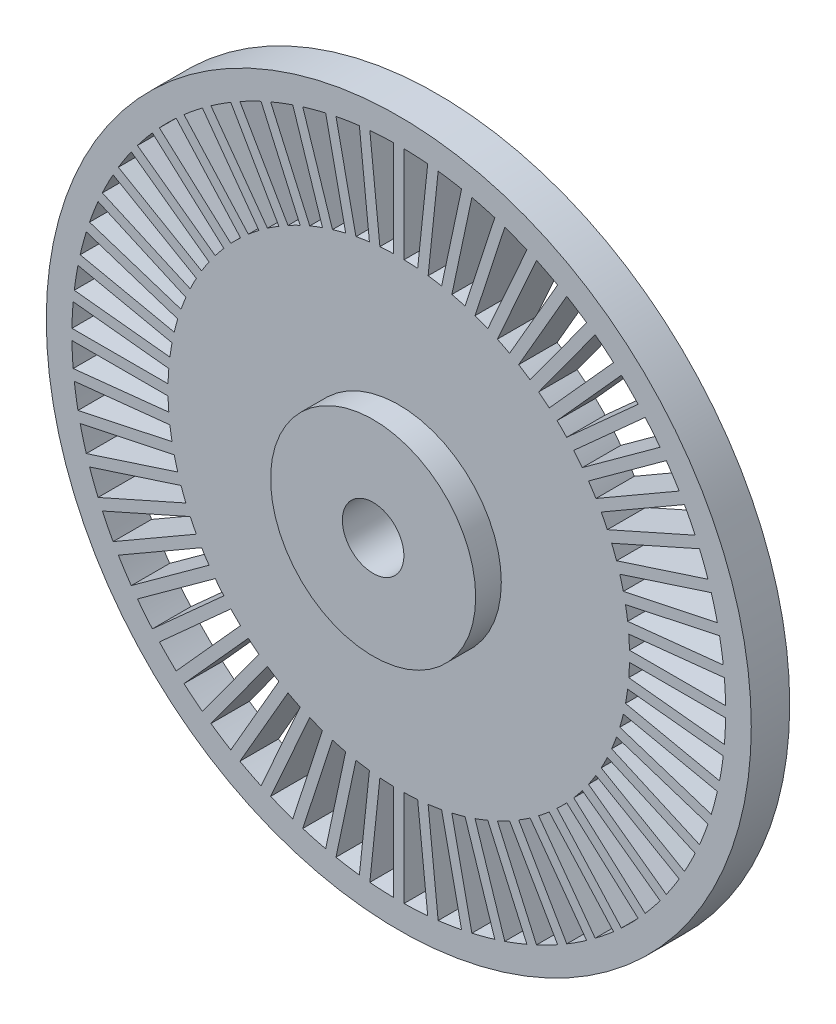
SolidWorks part; units mm, degrees
ref_plane "Płaszczyzna przednia" through (0, 0, 0) normal (0, 0, 1) x (1, 0, 0)
ref_plane "Płaszczyzna górna" through (0, 0, 0) normal (0, 1, 0) x (1, 0, 0)
ref_plane "Płaszczyzna prawa" through (0, 0, 0) normal (1, 0, 0) x (0, 0, -1)
sketch "Szkic1" plane through (0, 0, 0) normal (0, 0, 1) x (1, 0, 0)
  circle A0 centre (0, 0) radius 13.75
  circle A1 centre (0, 0) radius 1.2
  dimension "D1" = 27.5
  dimension "D2" = 2.4
extrude "Dodanie-wyciągnięcie1" add sketch "Szkic1" along normal blind 1.5
sketch "Szkic2" plane through (0, 0, 0) normal (0, 0, -1) x (-1, 0, 0)
  circle A0 centre (0, 0) radius 12.75
  circle A1 centre (0, 0) radius 9
  dimension "D1" = 25.5
  dimension "D2" = 18
extrude "Wytnij-wyciągnięcie1" cut sketch "Szkic2" against normal up to surface (1.5 mm away) up to face at (13.75, 0, 1.5)
sketch "Szkic3" plane through (0, 0, 1.5) normal (0, 0, 1) x (1, 0, 0)
  line L0 (0, 0) -> (0, 12.5303) construction
  line L2 (-0.205, 12.8997) -> (0.205, 12.8997)
  line L3 (-0.205, 12.8997) -> (-0.205, 8.1438)
  line L4 (-0.205, 8.1438) -> (0.205, 8.1438)
  line L5 (0.205, 12.8997) -> (0.205, 8.1438)
  line L6 (-0.205, 12.8997) -> (0.205, 8.1438) construction
  line L7 (-0.205, 8.1438) -> (0.205, 12.8997) construction
  point P3 (0, 10.5217)
  dimension "D1" = 0.41
extrude "Dodanie-wyciągnięcie2" add sketch "Szkic3" against normal up to surface (1.5 mm away) up to face at (1.2, 0, 0)
pattern_circular "Szyk kołowy1" count 60 every 6 about axis through (0, 0, 0) along (0, 0, 1) of "Dodanie-wyciągnięcie2"
sketch "Szkic4" plane through (0, 0, 1.5) normal (0, 0, 1) x (1, 0, 0)
  circle A0 centre (0, 0) radius 1.2
  circle A1 centre (0, 0) radius 4
  dimension "D1" = 8
extrude "Dodanie-wyciągnięcie3" add sketch "Szkic4" along normal blind 1
